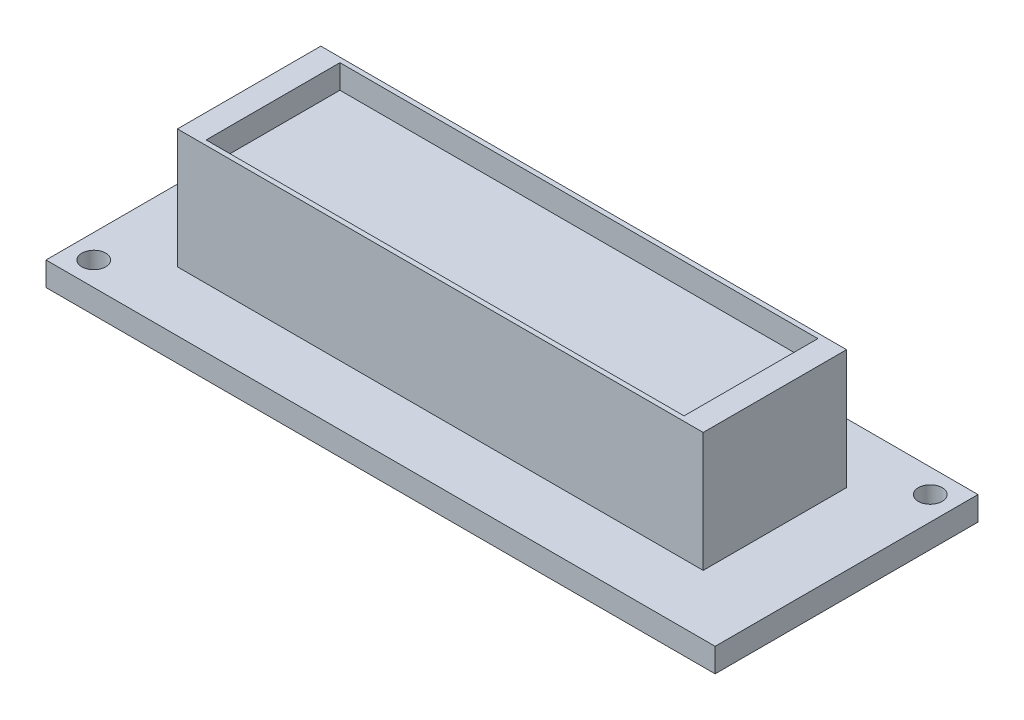
SolidWorks part; units mm, degrees
ref_plane "Front Plane" through (0, 0, 0) normal (0, 0, 1) x (1, 0, 0)
ref_plane "Top Plane" through (0, 0, 0) normal (0, 1, 0) x (1, 0, 0)
ref_plane "Right Plane" through (0, 0, 0) normal (1, 0, 0) x (0, 0, -1)
sketch "Sketch1" plane through (0, 0, 0) normal (0, 1, 0) x (1, 0, 0)
  line L0 (0, 0) -> (100, 0)
  line L1 (100, 0) -> (100, 28)
  line L2 (100, 28) -> (0, 28)
  line L3 (0, 28) -> (0, 0)
  dimension "D1" = 100
  dimension "D2" = 28
extrude "Boss-Extrude1" add sketch "Sketch1" along normal blind 1
sketch "Sketch2" plane through (0, 1, 0) normal (0, 1, 0) x (1, 0, 0)
  line L0 (50, 14) -> (105, 14)
  line L1 (105, 14) -> (105, 29)
  line L2 (105, 14) -> (105, -1)
  line L3 (105, 29) -> (-5, 29)
  line L4 (-5, 29) -> (-5, -1)
  line L5 (-5, -1) -> (105, -1)
  dimension "D1" = 55
  dimension "D2" = 15
  dimension "D3" = 15
  dimension "D4" = 110
extrude "Boss-Extrude2" add sketch "Sketch2" along normal blind 30 separate body
sketch "Sketch3" plane through (0, 1, 0) normal (0, -1, 0) x (1, 0, 0)
  line L0 (50, 1) -> (50, 3.5)
  line L1 (-5, 1) -> (105, 1) construction
  line L2 (50, 3.5) -> (110, 3.5)
  line L3 (50, 3.5) -> (-10, 3.5)
  line L5 (50, -29) -> (50, -31.5)
  line L6 (105, -29) -> (-5, -29) construction
  line L7 (50, -31.5) -> (-10, -31.5)
  line L8 (50, -31.5) -> (110, -31.5)
  line L9 (110, -31.5) -> (110, 3.5)
  line L10 (-10, -31.5) -> (-10, 3.5)
  line M1 (105, -29) -> (105, 1)
  line M2 (105, 1) -> (-5, 1)
  line M3 (-5, 1) -> (-5, -29)
  line M4 (-5, -29) -> (105, -29)
  dimension "D1" = 2.5
  dimension "D2" = 60
  dimension "D3" = 60
  dimension "D4" = 2.5
  dimension "D5" = 60
extrude "Boss-Extrude3" add sketch "Sketch3" against normal blind 5 contours L8 L9 L2 L0 L5 M2 M1 M4 | L10 L7 L5 L0 L3 M4 M3 M2
sketch "Sketch4" plane through (0, 6, 0) normal (0, 1, 0) x (1, 0, 0)
  line L0 (-20, 41.5) -> (-20, -13.5)
  line L1 (-20, -13.5) -> (120, -13.5)
  line L3 (-20, 41.5) -> (120, 41.5)
  line L4 (120, -13.5) -> (120, 41.5)
  line L6 (110, -13.5) -> (120, -13.5)
  point P0 (0, 0)
  line M5 (-10, -3.5) -> (110, -3.5)
  line M6 (110, -3.5) -> (110, 31.5)
  line M7 (110, 31.5) -> (-10, 31.5)
  line M8 (-10, 31.5) -> (-10, -3.5)
  line M9 (-5, -1) -> (-5, 29)
  line M10 (-5, 29) -> (105, 29)
  line M11 (105, 29) -> (105, -1)
  line M12 (105, -1) -> (-5, -1)
  dimension "D5" = 10
extrude "Boss-Extrude4" add sketch "Sketch4" against normal blind 5 contours L1 L4 L3 L0 M5 M8 M7 M6 | M8 M5 M6 M7 M12 M9 M10 M11
sketch "Sketch5" plane through (0, 1, 0) normal (0, 1, 0) x (1, 0, 0)
  line L0 (0, 28) -> (100, 28)
  line L1 (100, 28) -> (100, 0)
  line L2 (100, 0) -> (0, 0)
  line L3 (0, 0) -> (0, 28)
extrude "Boss-Extrude5" add sketch "Sketch5" along normal blind 25
sketch "Sketch6" plane through (0, 6, 0) normal (0, 1, 0) x (1, 0, 0)
  line L0 (120, 41.5) -> (115, 41.5)
  line L1 (-20, 41.5) -> (120, 41.5) construction
  line L2 (115, 41.5) -> (115, 36.5)
  line L3 (-20, -13.5) -> (-20, -8.5)
  line L4 (-20, 41.5) -> (-20, -13.5) construction
  line L5 (-20, -8.5) -> (-15, -8.5)
  circle A0 centre (115, 36.5) radius 2.5
  circle A1 centre (-15, -8.5) radius 2.5
  dimension "D3" = 5
  dimension "D6" = 5
  dimension "D1" = 5
  dimension "D2" = 5
  dimension "D4" = 5
  dimension "D5" = 5
extrude "Cut-Extrude1" cut sketch "Sketch6" against normal blind 25
